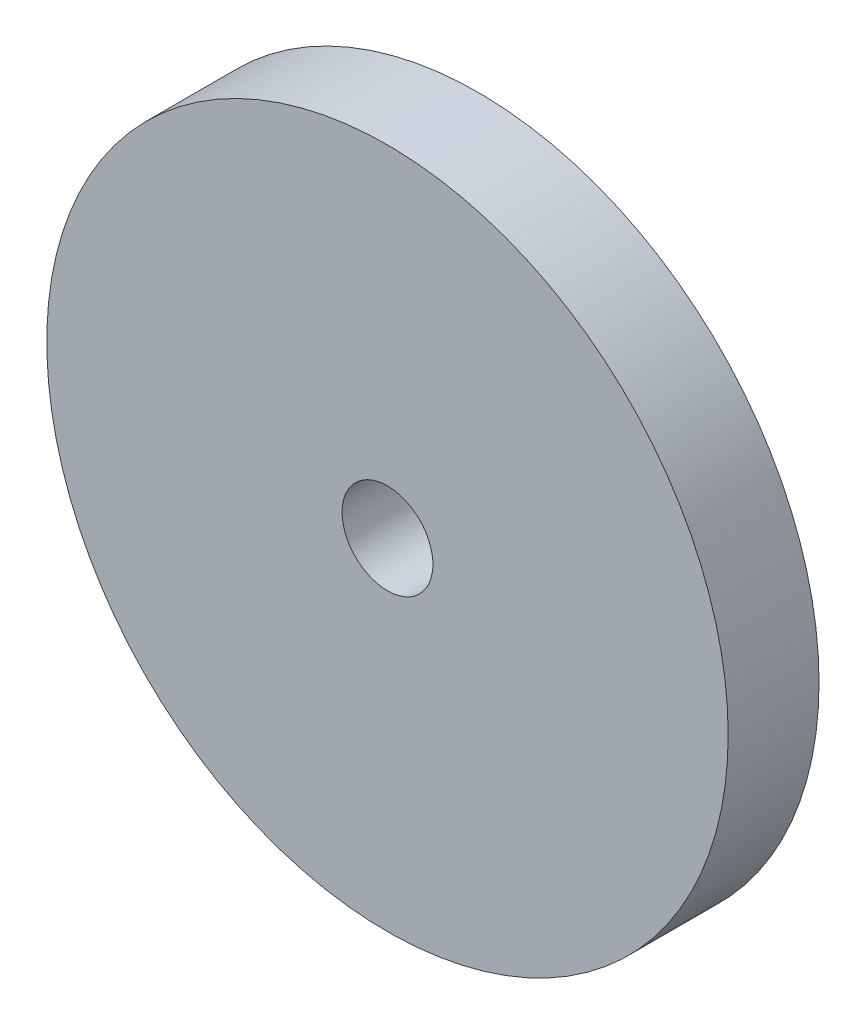
SolidWorks part; units mm, degrees
ref_plane "前视基准面" through (0, 0, 0) normal (0, 0, 1) x (1, 0, 0)
ref_plane "上视基准面" through (0, 0, 0) normal (0, 1, 0) x (1, 0, 0)
ref_plane "右视基准面" through (0, 0, 0) normal (1, 0, 0) x (0, 0, -1)
sketch "草图1" plane through (0, 0, 0) normal (0, 0, 1) x (1, 0, 0)
  circle A0 centre (-30.6409, 5.9506) radius 22.5
  dimension "D1" = 45
extrude "凸台-拉伸1" add sketch "草图1" along normal blind 10
sketch "草图2" plane through (0, 0, 10) normal (0, 0, 1) x (1, 0, 0)
  circle A1 centre (-30.6409, 5.9506) radius 37.5
  circle A2 centre (-30.6409, 5.9506) radius 22.5 construction
  dimension "D1" = 75
  dimension "D2" = 0
extrude "凸台-拉伸2" add sketch "草图2" along normal blind 10
sketch "草图3" plane through (0, 0, 0) normal (0, 0, -1) x (-1, 0, 0)
  circle A0 centre (30.6409, 5.9506) radius 5
extrude "切除-拉伸1" cut sketch "草图3" against normal blind 20
